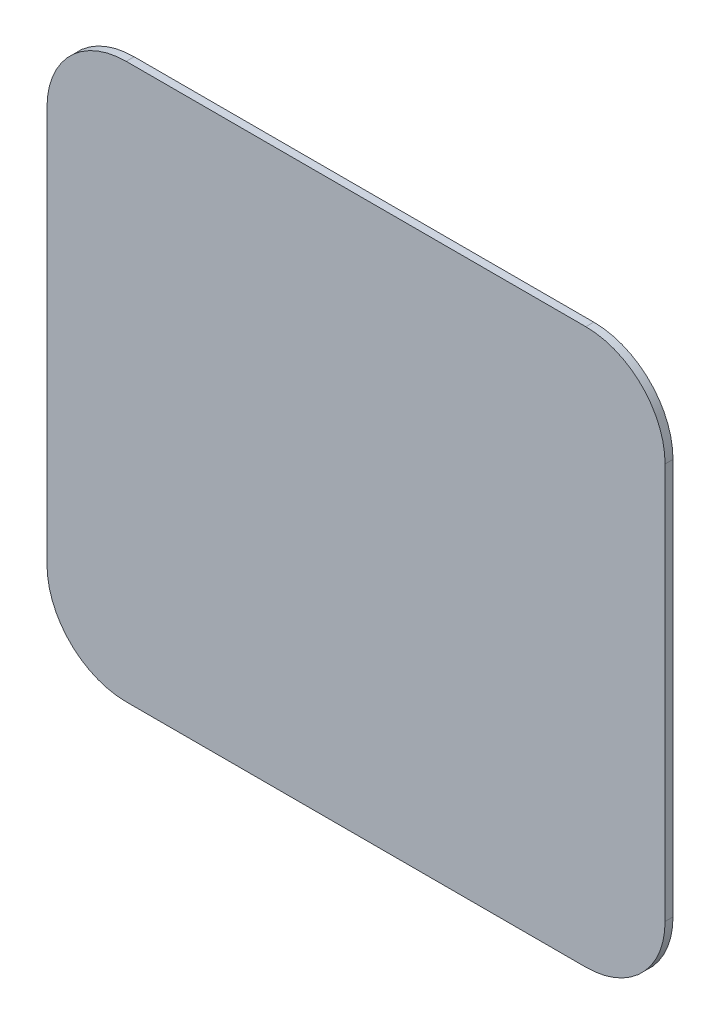
SolidWorks part; units mm, degrees
ref_plane "Front Plane" through (0, 0, 0) normal (0, 0, 1) x (1, 0, 0)
ref_plane "Top Plane" through (0, 0, 0) normal (0, 1, 0) x (1, 0, 0)
ref_plane "Right Plane" through (0, 0, 0) normal (1, 0, 0) x (0, 0, -1)
sketch "Sketch1" plane through (0, 0, 0) normal (0, 0, 1) x (1, 0, 0)
  line L0 (85.3333, 256) -> (81.5286, 231.264) construction
  line L1 (-153.9588, 7.6106) -> (187.3745, 7.6106) construction
  line L7 (-39.0754, 39.9502) -> (38.9246, 39.9502)
  line L8 (-39.0754, 39.9502) -> (-39.0754, -30.0498)
  line L9 (-39.0754, -30.0498) -> (38.9246, -30.0498)
  line L10 (38.9246, 39.9502) -> (38.9246, -30.0498)
  point P0 (0, 0)
  point P6 (0, 0)
  dimension "D1" = 78
  dimension "D2" = 70
extrude "Boss-Extrude1" add sketch "Sketch1" along normal blind 1
fillet "Fillet1" radius 10 4 edges at (-39.0754, 39.9502, 0.5) (-39.0754, -30.0498, 0.5) (38.9246, -30.0498, 0.5) (38.9246, 39.9502, 0.5)
